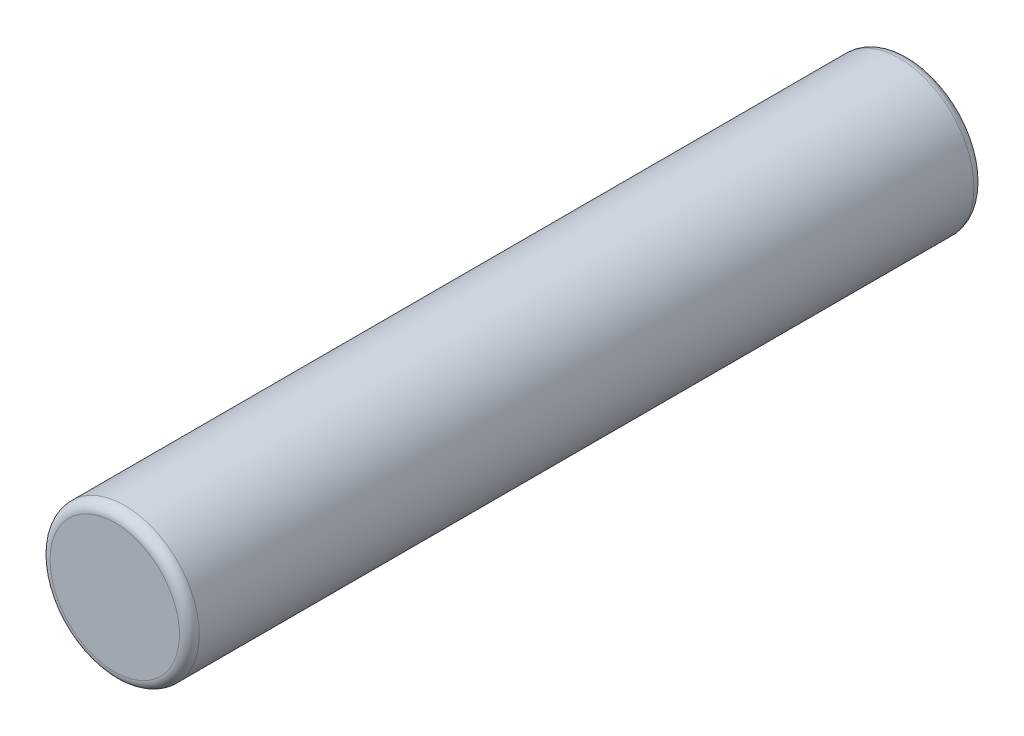
SolidWorks part; units mm, degrees
ref_plane "Face" through (0, 0, 0) normal (0, 0, 1) x (1, 0, 0)
ref_plane "Dessus" through (0, 0, 0) normal (0, 1, 0) x (1, 0, 0)
ref_plane "Droite" through (0, 0, 0) normal (1, 0, 0) x (0, 0, -1)
sketch "Esquisse1" plane through (0, 0, 0) normal (1, 0, 0) x (0, 0, -1)
  line L0 (0, 0) -> (0, 1.5025)
  line L1 (0, 1.5025) -> (16, 1.5025)
  line L2 (16, 1.5025) -> (16, 0)
  line L3 (0, 0) -> (108.1391, 0) construction
  line L4 (0, 0) -> (16, 0)
  dimension "D1" = 16
revolve "Révolution1" add sketch "Esquisse1" angle 360 about L3
fillet "Congé1" radius 0.2 1 edges at (1.5025, 0, -16)
fillet "Congé2" radius 0.2 1 edges at (1.5025, 0, 0)
